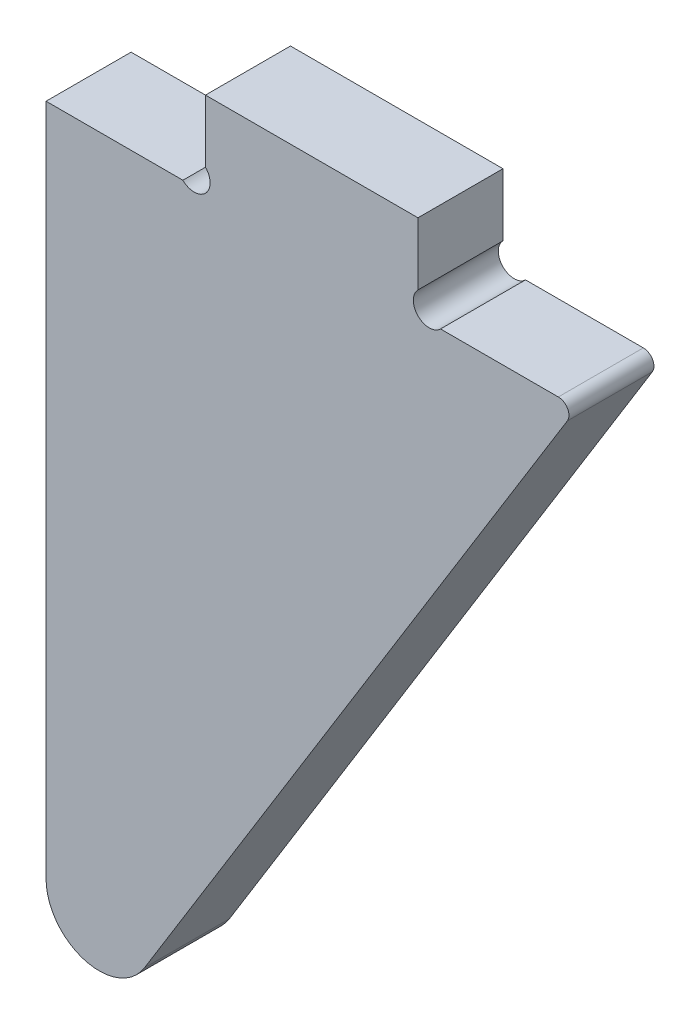
SolidWorks part; units mm, degrees
ref_plane "Plan de face" through (0, 0, 0) normal (0, 0, 1) x (1, 0, 0)
ref_plane "Plan de dessus" through (0, 0, 0) normal (0, 1, 0) x (1, 0, 0)
ref_plane "Plan de droite" through (0, 0, 0) normal (1, 0, 0) x (0, 0, -1)
sketch "Esquisse1" plane through (0, 0, 0) normal (0, 0, 1) x (1, 0, 0)
  line L0 (0, 0) -> (0, 81)
  line L1 (0, 81) -> (12.8787, 81)
  line L2 (15, 83.1213) -> (15, 89)
  line L3 (15, 89) -> (35, 89)
  line L4 (35, 89) -> (35, 83.1213)
  line L5 (37.1213, 81) -> (50, 81)
  line L6 (50, 81) -> (0, 0)
  arc A0 (12.8787, 81) -> (15, 83.1213) centre (13.9393, 82.0607) ccw
  arc A1 (35, 83.1213) -> (37.1213, 81) centre (36.0607, 82.0607) ccw
  dimension "D1" = 89
  dimension "D5" = 20
extrude "Boss.-Extru.1" add sketch "Esquisse1" along normal blind 8
fillet "Congé1" radius 5 1 edges at (0, 0, 4)
fillet "Congé2" radius 1 1 edges at (50, 81, 4)
